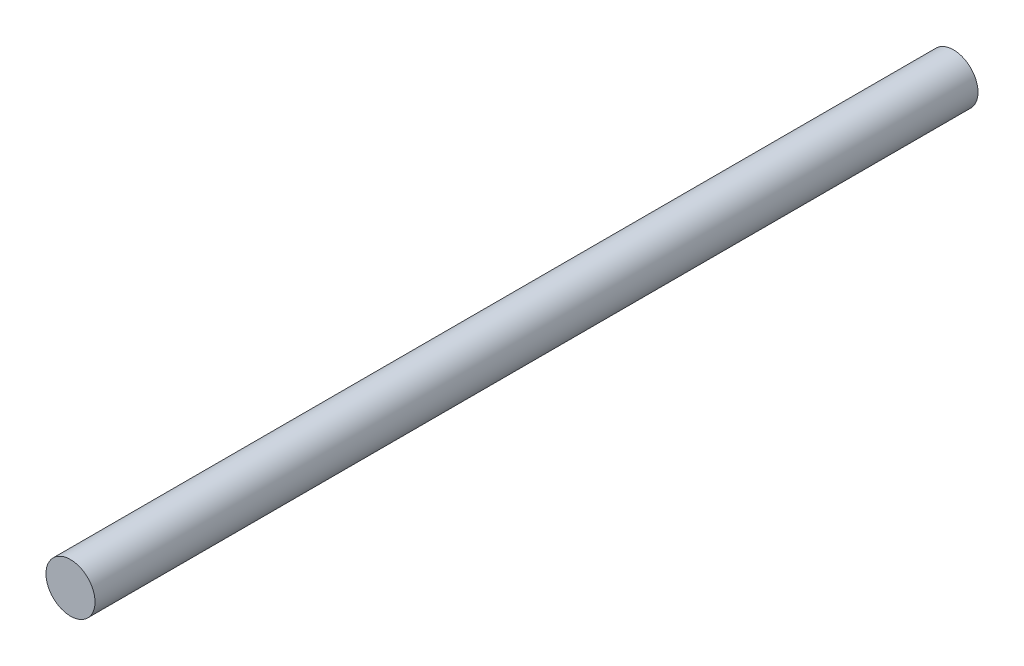
SolidWorks part; units mm, degrees
ref_plane "Front Plane" through (0, 0, 0) normal (0, 0, 1) x (1, 0, 0)
ref_plane "Top Plane" through (0, 0, 0) normal (0, 1, 0) x (1, 0, 0)
ref_plane "Right Plane" through (0, 0, 0) normal (1, 0, 0) x (0, 0, -1)
sketch "Sketch1" plane through (0, 0, 0) normal (0, 0, 1) x (1, 0, 0)
  circle A0 centre (0, 0) radius 3.175
  dimension "D1" = 6.35
extrude "Boss-Extrude1" add sketch "Sketch1" along normal blind 114.3 contours A0
